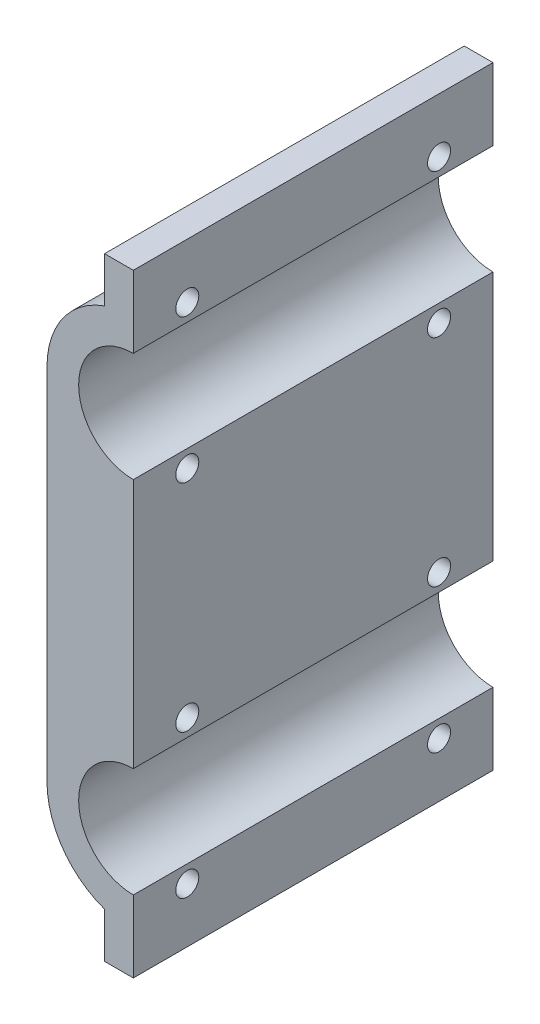
SolidWorks part; units mm, degrees
ref_plane "Plano frontal" through (0, 0, 0) normal (0, 0, 1) x (1, 0, 0)
ref_plane "Plano superior" through (0, 0, 0) normal (0, 1, 0) x (1, 0, 0)
ref_plane "Plano direito" through (0, 0, 0) normal (1, 0, 0) x (0, 0, -1)
sketch "Esboço1" plane through (0, 0, 0) normal (0, 0, 1) x (1, 0, 0)
  line L0 (0, 17.4) -> (0, -17.4) construction
  line L1 (0, 17.4) -> (0, -17.4)
  line L2 (-12, 25) -> (-12, -25)
  line L3 (0, -32.6) -> (0, -42.6)
  line L4 (0, -42.6) -> (-4, -42.6)
  line L5 (-4, -42.6) -> (-4, -36.3137)
  line L6 (0, 32.6) -> (0, 42.6)
  line L7 (0, 42.6) -> (-4, 42.6)
  line L8 (-4, 42.6) -> (-4, 36.3137)
  arc A0 (0, 32.6) -> (0, 17.4) centre (0, 25) ccw
  arc A1 (0, -17.4) -> (0, -32.6) centre (0, -25) ccw
  arc A2 (-4, 36.3137) -> (-12, 25) centre (0, 25) ccw
  arc A3 (-12, -25) -> (-4, -36.3137) centre (0, -25) ccw
  point P5 (0, 0)
  point P15 (0, 0)
  dimension "D1" = 15.2
  dimension "D2" = 12
  dimension "D3" = 50
  dimension "D4" = 10
  dimension "D5" = 4
extrude "Ressalto-extrusão1" add sketch "Esboço1" along normal blind 50
sketch "Esboço2" plane through (0, 0, 0) normal (1, 0, 0) x (0, 0, -1)
  line L0 (-50, 25) -> (0, 25) construction
  line L1 (-50, -25) -> (0, -25) construction
  line L2 (-50, -17.4) -> (-50, -32.6) construction
  line L3 (0, -32.6) -> (0, -17.4) construction
  line L4 (-25, 42.6) -> (-25, -42.6) construction
  line L5 (-50, 42.6) -> (0, 42.6) construction
  line L6 (-50, -42.6) -> (0, -42.6) construction
  circle A0 centre (-42.5, 35) radius 1.6
  circle A1 centre (-7.5, 35) radius 1.6
  circle A2 centre (-7.5, -35) radius 1.6
  circle A3 centre (-42.5, -35) radius 1.6
  circle A4 centre (-42.5, -15) radius 1.6
  circle A5 centre (-42.5, 15) radius 1.6
  circle A6 centre (-7.5, 15) radius 1.6
  circle A7 centre (-7.5, -15) radius 1.6
  point P32 (-44.2775, 37.7044)
  point P33 (-40.3086, 37.591)
  point P34 (0, 0)
  point P35 (0, 0)
  dimension "D4" = 3.2
  dimension "D1" = 20
  dimension "D2" = 20
  dimension "D3" = 35
extrude "Corte-extrusão1" cut sketch "Esboço2" against normal through all
sketch "Esboço3" plane through (-12, 0, 0) normal (-1, 0, 0) x (0, 0, 1)
  line L0 (0, 25) -> (0, -25) construction
  line L1 (10.25, 36.5877) -> (7.5, 38.1754)
  line L2 (7.5, 38.1754) -> (4.75, 36.5877)
  line L3 (4.75, 36.5877) -> (4.75, 33.4123)
  line L4 (4.75, 33.4123) -> (7.5, 31.8246)
  line L5 (7.5, 31.8246) -> (10.25, 33.4123)
  line L6 (10.25, 33.4123) -> (10.25, 36.5877)
  line L7 (45.25, 36.5877) -> (42.5, 38.1754)
  line L8 (42.5, 38.1754) -> (39.75, 36.5877)
  line L9 (39.75, 36.5877) -> (39.75, 33.4123)
  line L10 (39.75, 33.4123) -> (42.5, 31.8246)
  line L11 (42.5, 31.8246) -> (45.25, 33.4123)
  line L12 (45.25, 33.4123) -> (45.25, 36.5877)
  line L13 (45.25, 16.5877) -> (42.5, 18.1754)
  line L14 (42.5, 18.1754) -> (39.75, 16.5877)
  line L15 (39.75, 16.5877) -> (39.75, 13.4123)
  line L16 (39.75, 13.4123) -> (42.5, 11.8246)
  line L17 (42.5, 11.8246) -> (45.25, 13.4123)
  line L18 (45.25, 13.4123) -> (45.25, 16.5877)
  line L19 (10.25, 16.5877) -> (7.5, 18.1754)
  line L20 (7.5, 18.1754) -> (4.75, 16.5877)
  line L21 (4.75, 16.5877) -> (4.75, 13.4123)
  line L22 (4.75, 13.4123) -> (7.5, 11.8246)
  line L23 (7.5, 11.8246) -> (10.25, 13.4123)
  line L24 (10.25, 13.4123) -> (10.25, 16.5877)
  line L25 (10.25, -13.4123) -> (7.5, -11.8246)
  line L26 (7.5, -11.8246) -> (4.75, -13.4123)
  line L27 (4.75, -13.4123) -> (4.75, -16.5877)
  line L28 (4.75, -16.5877) -> (7.5, -18.1754)
  line L29 (7.5, -18.1754) -> (10.25, -16.5877)
  line L30 (10.25, -16.5877) -> (10.25, -13.4123)
  line L31 (10.25, -33.4123) -> (7.5, -31.8246)
  line L32 (7.5, -31.8246) -> (4.75, -33.4123)
  line L33 (4.75, -33.4123) -> (4.75, -36.5877)
  line L34 (4.75, -36.5877) -> (7.5, -38.1754)
  line L35 (7.5, -38.1754) -> (10.25, -36.5877)
  line L36 (10.25, -36.5877) -> (10.25, -33.4123)
  line L37 (45.25, -33.4123) -> (42.5, -31.8246)
  line L38 (42.5, -31.8246) -> (39.75, -33.4123)
  line L39 (39.75, -33.4123) -> (39.75, -36.5877)
  line L40 (39.75, -36.5877) -> (42.5, -38.1754)
  line L41 (42.5, -38.1754) -> (45.25, -36.5877)
  line L42 (45.25, -36.5877) -> (45.25, -33.4123)
  line L43 (45.25, -13.4123) -> (42.5, -11.8246)
  line L44 (42.5, -11.8246) -> (39.75, -13.4123)
  line L45 (39.75, -13.4123) -> (39.75, -16.5877)
  line L46 (39.75, -16.5877) -> (42.5, -18.1754)
  line L47 (42.5, -18.1754) -> (45.25, -16.5877)
  line L48 (45.25, -16.5877) -> (45.25, -13.4123)
  circle A0 centre (7.5, 35) radius 2.75 construction
  circle A1 centre (42.5, 35) radius 2.75 construction
  circle A2 centre (42.5, 15) radius 2.75 construction
  circle A3 centre (7.5, 15) radius 2.75 construction
  circle A4 centre (7.5, -15) radius 2.75 construction
  circle A5 centre (7.5, -35) radius 2.75 construction
  circle A6 centre (42.5, -35) radius 2.75 construction
  circle A7 centre (42.5, -15) radius 2.75 construction
  point P64 (17.6358, -15)
  point P73 (10.995, -8.8029)
  point P74 (15.1345, -15)
  point P77 (12.1822, -12.2967)
  dimension "D1" = 5.5
extrude "Corte-extrusão2" cut sketch "Esboço3" against normal offset from surface 4 draft 2
equation "\"D2@Esboço2\"=\"D1@Esboço2\""
